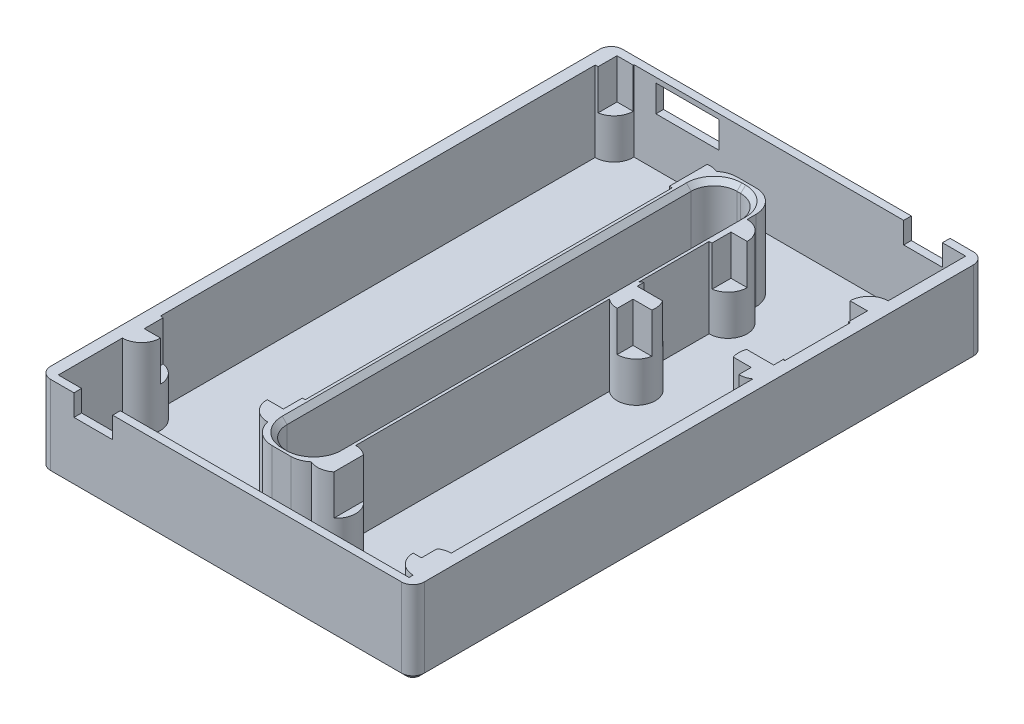
SolidWorks part; units mm, degrees
ref_plane "Front Plane" through (0, 0, 0) normal (0, 0, 1) x (1, 0, 0)
ref_plane "Top Plane" through (0, 0, 0) normal (0, 1, 0) x (1, 0, 0)
ref_plane "Right Plane" through (0, 0, 0) normal (1, 0, 0) x (0, 0, -1)
sketch "Sketch2" plane through (0, 0, 0) normal (0, 1, 0) x (1, 0, 0)
  line L1 (23, -37.5) -> (-23, -37.5)
  line L2 (24.5, -36) -> (24.5, 36)
  line L3 (23, 37.5) -> (-23, 37.5)
  line L4 (-24.5, -36) -> (-24.5, 36)
  line L5 (24.5, -37.5) -> (-24.5, 37.5) construction
  line L6 (24.5, 37.5) -> (-24.5, -37.5) construction
  line L15 (22.2754, -34.095) -> (-23.4369, 35.8728) construction
  line L16 (21.5, 35.8333) -> (-21.5, -35.8333) construction
  line L17 (23, -36.5) -> (-23, -36.5)
  line L18 (23, -36.5) -> (23, 36.5)
  line L19 (23, 36.5) -> (-23, 36.5)
  line L20 (-23, -36.5) -> (-23, 36.5)
  line L21 (23, -36.5) -> (-23, 36.5) construction
  line L22 (23, 36.5) -> (-23, -36.5) construction
  line L23 (0, 29.5) -> (0.5, 29.5)
  line L24 (-3, 26.5) -> (-3, -26.5)
  line L25 (0, -29.5) -> (0.5, -29.5)
  line L26 (3.5, 26.5) -> (3.5, -26.5)
  arc A0 (0.5, -29.5) -> (3.5, -26.5) centre (0.5, -26.5) ccw
  arc A1 (-3, -26.5) -> (0, -29.5) centre (0, -26.5) ccw
  arc A2 (0, 29.5) -> (-3, 26.5) centre (0, 26.5) ccw
  arc A3 (0.5, 29.5) -> (3.5, 26.5) centre (0.5, 26.5) cw
  arc A4 (-23, -37.5) -> (-24.5, -36) centre (-23, -36) cw
  arc A5 (23, -37.5) -> (24.5, -36) centre (23, -36) ccw
  arc A6 (24.5, 36) -> (23, 37.5) centre (23, 36) ccw
  arc A7 (-23, 37.5) -> (-24.5, 36) centre (-23, 36) ccw
  point P0 (0, 0)
  point P6 (0, 0)
  point P15 (-14.0764, 21.5455)
  point P18 (3.5, -29.5)
  point P20 (0, 0)
  point P26 (-3, -29.5)
  dimension "D3" = 46
  dimension "D7" = 3
  dimension "D5" = 1.5
  dimension "D1" = 75
  dimension "D2" = 49
  dimension "D4" = 73
  dimension "20" = 20
  dimension "D6" = 6.5
  dimension "D8" = 7
  dimension "D9" = 53
extrude "Boss-Extrude1" add sketch "Sketch2" against normal blind 11 contours L4 L1 L2 L3 L17 L20 L19 L18 | L20 L17 L18 L19 L23 A3 L26 A0 L25 A1 L24 A2
sketch "Sketch8" plane through (0, 0, 0) normal (0, 1, 0) x (1, 0, 0)
  line L1 (23, -36.5) -> (-23, -36.5)
  line L2 (23, -36.5) -> (23, 36.5)
  line L3 (23, 36.5) -> (-23, 36.5)
  line L4 (-23, -36.5) -> (-23, 36.5)
  line L5 (23, -36.5) -> (-23, 36.5) construction
  line L6 (23, 36.5) -> (-23, -36.5) construction
  line L8 (23, -36.5) -> (23, 36.5) construction
  line L9 (23, 36.5) -> (-23, 36.5) construction
  line L10 (-3, 26.5) -> (-3, -26.5) construction
  line L11 (0, 29.5) -> (0.5, 29.5)
  line L12 (-3, 26.5) -> (-3, -26.5)
  line L13 (0, -29.5) -> (0.5, -29.5)
  line L14 (3.5, 26.5) -> (3.5, -26.5)
  line L15 (3.5, 26.5) -> (3.5, -26.5) construction
  line L17 (-1, 30.5) -> (1.5, 30.5)
  line L18 (-4, 27.5) -> (-4, -27.5)
  line L19 (-1, -30.5) -> (1.5, -30.5)
  line L20 (4.5, 27.5) -> (4.5, -27.5)
  arc A0 (-3, -26.5) -> (0, -29.5) centre (0, -26.5) ccw
  arc A1 (0.5, -29.5) -> (3.5, -26.5) centre (0.5, -26.5) ccw
  arc A2 (0.5, 29.5) -> (3.5, 26.5) centre (0.5, 26.5) cw
  arc A3 (0, 29.5) -> (-3, 26.5) centre (0, 26.5) ccw
  arc A4 (-4, -27.5) -> (-1, -30.5) centre (-1, -27.5) ccw
  arc A5 (1.5, -30.5) -> (4.5, -27.5) centre (1.5, -27.5) ccw
  arc A6 (1.5, 30.5) -> (4.5, 27.5) centre (1.5, 27.5) cw
  arc A7 (-1, 30.5) -> (-4, 27.5) centre (-1, 27.5) ccw
  point P0 (0, 0)
  dimension "D3" = 3
  dimension "D9" = 3
  dimension "D1" = 7
  dimension "D2" = 19
  dimension "D4" = 6.5
  dimension "D5" = 1
  dimension "D6" = 1
  dimension "D7" = 1
  dimension "D8" = 1
extrude "Cut-Extrude1" cut sketch "Sketch8" against normal blind 10.5 contours L2 L1 L4 L3 | L12 A0 L13 A1 L14 A2 L11 A3 | L18 A4 L19 A5 L20 A6 L17 A7
sketch "Sketch9" plane through (0, -10.5, 0) normal (0, 1, 0) x (1, 0, 0)
  line L0 (21.58, 9.7933) -> (21.58, 11.5426) construction
  line L1 (-4.375, -25.6053) -> (-22.625, -25.6053) construction
  line L2 (-4.375, -25.6053) -> (-4.375, 36.3947) construction
  line L3 (-4.375, 36.3947) -> (-22.625, 36.3947) construction
  line L4 (-22.625, -25.6053) -> (-22.625, 36.3947) construction
  line L5 (-4.375, -25.6053) -> (-22.625, 36.3947) construction
  line L6 (-4.375, 36.3947) -> (-22.625, -25.6053) construction
  line L7 (4.875, 23.8426) -> (22.775, 23.8426) construction
  line L8 (4.875, 23.8426) -> (4.875, 11.5426) construction
  line L9 (4.875, 11.5426) -> (22.775, 11.5426) construction
  line L10 (22.775, 23.8426) -> (22.775, 11.5426) construction
  line L11 (4.875, 23.8426) -> (22.775, 11.5426) construction
  line L12 (4.875, 11.5426) -> (22.775, 23.8426) construction
  line L13 (6.08, 9.7933) -> (21.58, 9.7933) construction
  line L14 (6.08, 9.7933) -> (6.08, -33.4567) construction
  line L15 (6.08, -33.4567) -> (21.58, -33.4567) construction
  line L16 (21.58, 9.7933) -> (21.58, -33.4567) construction
  line L17 (6.08, 9.7933) -> (21.58, -33.4567) construction
  line L18 (6.08, -33.4567) -> (21.58, 9.7933) construction
  line L19 (6.08, 8.888) -> (6.08, 11.5426) construction
  line L20 (4.5, 27.5) -> (4.5, -27.5) construction
  line L21 (23, -36.5) -> (23, 36.5) construction
  line L22 (4.5, 27.5) -> (4.5, -27.5) construction
  line L23 (23, -36.5) -> (23, 36.5) construction
  line L24 (-4, 27.5) -> (-4, -27.5) construction
  line L25 (-23, -36.5) -> (-23, 36.5) construction
  line L42 (24.5, -36) -> (24.5, 36) construction
  line L43 (-24.5, -36) -> (-24.5, 36) construction
  line L44 (23, 37.5) -> (-23, 37.5) construction
  line L45 (24.5, -35.4567) -> (24.5, -31.4567)
  line L46 (4.5, 26.3426) -> (4.5, 21.3426)
  line L47 (-4, 27.5) -> (-4, 25)
  line L48 (-24.5, -27.6053) -> (-24.5, -23.6053)
  line L49 (-20.7576, 37.5) -> (-23, 37.5)
  line L50 (-24.5, 34.3947) -> (-24.5, 36)
  line L51 (24.5, 21.8426) -> (24.5, 25.8426)
  line L52 (4.5, 12.1527) -> (4.5, 8.2779)
  line L53 (-4, -23.1053) -> (-4, -27.5)
  line L54 (4.5, -25) -> (4.5, -27.5)
  line L55 (-23, 5.3947) -> (-22.625, 5.3947) construction
  line L56 (-4.375, 5.3947) -> (-4, 5.3947) construction
  line L57 (-4, 27.5) -> (-4, -27.5) construction
  arc A0 (4.5, 21.3426) -> (4.5, 26.3426) centre (4.5, 23.8426) ccw
  arc A1 (24.5, 25.8426) -> (24.5, 21.8426) centre (23, 23.8426) ccw
  circle A3 centre (21.58, 10.6679) radius 2.5
  circle A4 centre (6.08, 10.2153) radius 2.5
  arc A5 (24.5, -31.4567) -> (24.5, -35.4567) centre (23, -33.4567) ccw
  arc A6 (3.4583, -29.7726) -> (4.5, -25) centre (4.5, -27.5) ccw
  arc A7 (-4, -23.1053) -> (-3.9385, -28.1045) centre (-4, -25.6053) ccw
  arc A8 (-24.5, -27.6053) -> (-24.5, -23.6053) centre (-23, -25.6053) ccw
  arc A9 (-24.5, 34.3947) -> (-20.7576, 37.5) centre (-23, 36.3947) ccw
  arc A10 (-2.9583, 29.7726) -> (-4, 25) centre (-4, 27.5) ccw
  arc A27 (-4, -27.5) -> (-1, -30.5) centre (-1, -27.5) ccw construction
  arc A28 (1.5, -30.5) -> (4.5, -27.5) centre (1.5, -27.5) ccw construction
  arc A29 (4.5, 27.5) -> (1.5, 30.5) centre (1.5, 27.5) ccw construction
  arc A30 (-1, 30.5) -> (-4, 27.5) centre (-1, 27.5) ccw construction
  arc A31 (-23, 37.5) -> (-24.5, 36) centre (-23, 36) ccw construction
  arc A32 (-4, -27.5) -> (-3.9385, -28.1045) centre (-1, -27.5) ccw
  arc A33 (3.4583, -29.7726) -> (4.5, -27.5) centre (1.5, -27.5) ccw
  arc A34 (4.5, 27.5) -> (1.5, 30.5) centre (1.5, 27.5) ccw
  arc A35 (-2.9583, 29.7726) -> (-4, 27.5) centre (-1, 27.5) ccw
  arc A36 (-23, 37.5) -> (-24.5, 36) centre (-23, 36) ccw
  point P0 (-13.5, 5.3947)
  point P5 (13.825, 17.6926)
  point P10 (13.83, -11.8317)
  dimension "D8" = 1.58
  dimension "D10" = 5
  dimension "D1" = 62
  dimension "D2" = 18.25
  dimension "D3" = 17.9
  dimension "D4" = 43.25
  dimension "D5" = 15.5
  dimension "D6" = 12.3
  dimension "D7" = 0.375
extrude "Boss-Extrude2" add sketch "Sketch9" along normal up to surface (10.5 mm away) contours L47 A10 A35 | A36 L50 A9 L49 | L46 A0 | A1 L51 | A3 | A4 | L45 A5 | L53 A32 A7 | L48 A8 | A33 L54 A6 up to face at (0, 0, 0)
ref_plane "Plane1" through (0, -5.25, 0) normal (0, 1, 0) x (1, 0, 0)
sketch "Sketch10" plane through (0, -5.25, 0) normal (0, 1, 0) x (1, 0, 0)
  line L0 (6.08, -33.4567) -> (21.58, -33.4567) construction
  line L1 (21.58, 9.7933) -> (21.58, -33.4567) construction
  line L2 (6.08, 9.7933) -> (6.08, -33.4567) construction
  line L3 (6.08, 9.7933) -> (21.58, 9.7933) construction
  line L4 (22.775, 23.8426) -> (22.775, 11.5426) construction
  line L5 (4.875, 11.5426) -> (22.775, 11.5426) construction
  line L6 (4.875, 23.8426) -> (4.875, 11.5426) construction
  line L7 (4.875, 23.8426) -> (22.775, 23.8426) construction
  line L8 (-4.375, -25.6053) -> (-22.625, -25.6053) construction
  line L9 (-22.625, -25.6053) -> (-22.625, 36.3947) construction
  line L10 (-4.375, -25.6053) -> (-4.375, 36.3947) construction
  line L11 (-4.375, 36.3947) -> (-22.625, 36.3947) construction
  line L12 (6.08, -33.4567) -> (21.58, -33.4567)
  line L13 (21.58, 9.7933) -> (21.58, -33.4567)
  line L14 (6.08, 9.7933) -> (6.08, -33.4567)
  line L15 (6.08, 9.7933) -> (21.58, 9.7933)
  line L16 (22.775, 23.8426) -> (22.775, 11.5426)
  line L17 (4.875, 11.5426) -> (22.775, 11.5426)
  line L18 (4.875, 23.8426) -> (4.875, 11.5426)
  line L19 (4.875, 23.8426) -> (22.775, 23.8426)
  line L20 (-4.375, -25.6053) -> (-22.625, -25.6053)
  line L21 (-22.625, -25.6053) -> (-22.625, 36.3947)
  line L22 (-4.375, -25.6053) -> (-4.375, 36.3947)
  line L23 (-4.375, 36.3947) -> (-22.625, 36.3947)
extrude "Cut-Extrude3" cut sketch "Sketch10" along normal up to surface (5.25 mm away) up to face at (0, 0, 0)
sketch "Sketch14" plane through (0, 0, -36.5) normal (0, 0, 1) x (1, 0, 0)
  line L1 (-9.375, -4.15) -> (-17.625, -4.15)
  line L2 (-9.375, -4.15) -> (-9.375, -0.65)
  line L3 (-9.375, -0.65) -> (-17.625, -0.65)
  line L4 (-17.625, -4.15) -> (-17.625, -0.65)
  line L5 (-9.375, -4.15) -> (-17.625, -0.65) construction
  line L6 (-9.375, -0.65) -> (-17.625, -4.15) construction
  line L7 (26.95, -5.25) -> (-26.95, -5.25) construction
  point P0 (-13.5, -2.4)
  dimension "D1" = 4.6
  dimension "D2" = 9.125
  dimension "D3" = 8.25
  dimension "D4" = 3.5
extrude "Cut-Extrude6" cut sketch "Sketch14" against normal blind 5
sketch "Sketch15" plane through (0, 0, -37.5) normal (0, 0, -1) x (-1, 0, 0)
  line L0 (23, -10.5) -> (23, 0) construction
  line L1 (-19.952, -2.794) -> (-14.872, -2.794)
  line L2 (-19.952, -2.794) -> (-19.952, 0)
  line L3 (-19.952, 0) -> (-14.872, 0)
  line L4 (-14.872, -2.794) -> (-14.872, 0)
  line L5 (-23, -10.5) -> (-23, 0) construction
  line L7 (23, -10.5) -> (23, 0)
  line L8 (-23, -10.5) -> (-23, 0)
  line L10 (-23, 0) -> (23, 0) construction
  line L11 (19.952, 0) -> (14.872, 0)
  line L12 (19.952, 0) -> (19.952, -2.794)
  line L13 (19.952, -2.794) -> (14.872, -2.794)
  line L14 (14.872, 0) -> (14.872, -2.794)
  dimension "D2" = 3.048
  dimension "D3" = 2.794
  dimension "D4" = 5.08
  dimension "D6" = 3.048
extrude "Cut-Extrude7" cut sketch "Sketch15" against normal up to next contours L1 L4 L3 L2
sketch "Sketch16" plane through (0, 0, 37.5) normal (0, 0, 1) x (1, 0, 0)
  line L0 (19.952, -2.794) -> (19.952, 0) construction
  line L1 (19.952, 0) -> (14.872, 0) construction
  line L2 (14.872, -2.794) -> (14.872, 0) construction
  line L3 (19.952, -2.794) -> (14.872, -2.794) construction
  line L4 (-14.872, 0) -> (-14.872, -2.794) construction
  line L5 (-19.952, 0) -> (-14.872, 0) construction
  line L6 (-19.952, 0) -> (-19.952, -2.794) construction
  line L7 (-19.952, -2.794) -> (-14.872, -2.794) construction
  line L8 (19.952, -2.794) -> (19.952, 0)
  line L9 (19.952, 0) -> (14.872, 0)
  line L10 (14.872, -2.794) -> (14.872, 0)
  line L11 (19.952, -2.794) -> (14.872, -2.794)
  line L12 (-14.872, 0) -> (-14.872, -2.794)
  line L13 (-19.952, 0) -> (-14.872, 0)
  line L14 (-19.952, 0) -> (-19.952, -2.794)
  line L15 (-19.952, -2.794) -> (-14.872, -2.794)
extrude "Cut-Extrude8" cut sketch "Sketch16" against normal up to next contours L15 L12 L13 L14
chamfer "Chamfer1" distance 0.635 angle 45 24 edges at (2.6213, -11, -28.6213) (3.5, -11, 0) (2.6213, -11, 28.6213) (0.25, -11, 29.5) (-2.1213, -11, 28.6213) (-3, -11, 0) (-2.1213, -11, -28.6213) (0.25, -11, -29.5) (-24.0607, -11, -37.0607) (-24.5, -11, 0) (-24.0607, -11, 37.0607) (0, -11, 37.5) (24.0607, -11, 37.0607) (24.5, -11, 0) (24.0607, -11, -37.0607) (0, -11, -37.5) (-3, 0, 0) (-2.1213, 0, -28.6213) (-2.1213, 0, 28.6213) (0.25, 0, -29.5) (0.25, 0, 29.5) (2.6213, 0, -28.6213) (2.6213, 0, 28.6213) (3.5, 0, 0)
